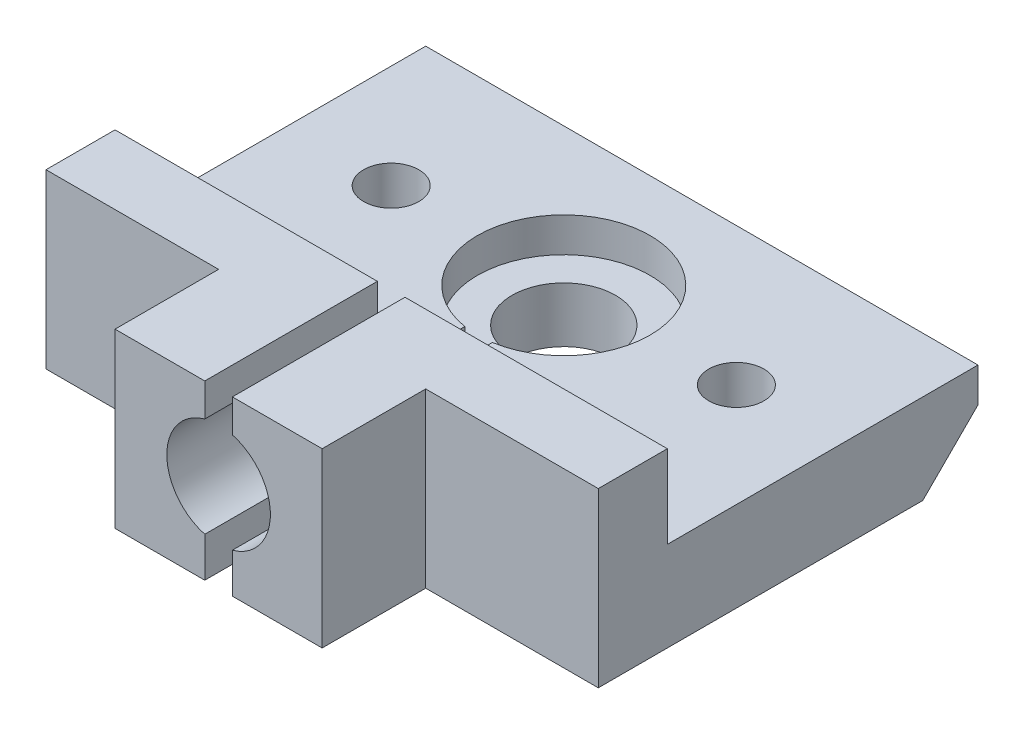
SolidWorks part; units mm, degrees
material "1060 Alloy"
ref_plane "Front Plane" through (0, 0, 0) normal (0, 0, 1) x (1, 0, 0)
ref_plane "Top Plane" through (0, 0, 0) normal (0, 1, 0) x (1, 0, 0)
ref_plane "Right Plane" through (0, 0, 0) normal (1, 0, 0) x (0, 0, -1)
sketch "Sketch1" plane through (0, 0, 0) normal (0, 1, 0) x (1, 0, 0)
  line L0 (0, 0) -> (85.3601, 0) construction
  line L1 (25, 0) -> (55, 0)
  line L2 (0, 15) -> (0, 70)
  line L3 (0, 70) -> (80, 70)
  line L4 (80, 15) -> (80, 70)
  line L7 (0, 15) -> (25, 15)
  line L8 (25, 0) -> (25, 15)
  line L10 (55, 0) -> (55, 15)
  line L11 (55, 15) -> (80, 15)
  line L13 (0, 0) -> (0, 88.5762) construction
  dimension "D1" = 80
  dimension "D2" = 70
  dimension "D3" = 25
  dimension "D4" = 25
  dimension "D5" = 15
  dimension "D6" = 15
extrude "Boss-Extrude1" add sketch "Sketch1" along normal blind 25 contours L4 L3 L2 L7 L8 L1 L10 L11
sketch "Sketch2" plane through (0, 0, 0) normal (1, 0, 0) x (0, 0, -1)
  line L1 (70, 25) -> (25, 25)
  line L2 (70, 25) -> (70, 13)
  line L3 (70, 13) -> (25, 13)
  line L4 (25, 25) -> (25, 13)
  dimension "D1" = 45
  dimension "D2" = 12
extrude "Cut-Extrude2" cut sketch "Sketch2" against normal through all and the other way through all contours L3 L4 L1 L2
chamfer "Chamfer1" distance 8 angle 45 1 edges at (40, 0, -70)
sketch "Sketch3" plane through (0, 13, 0) normal (0, 1, 0) x (1, 0, 0)
  line L0 (40, 0) -> (40, 55.2603) construction
  line L1 (25, 0) -> (55, 0) construction
  line L2 (0, 25) -> (80, 25) construction
  circle A0 centre (40, 50) radius 7.5
  circle A1 centre (65, 50) radius 4
  circle A2 centre (15, 50) radius 4
  point P10 (0, 0)
  dimension "D3" = 8
  dimension "D4" = 8
  dimension "D5" = 15
  dimension "D1" = 25
  dimension "D2" = 25
  dimension "D6" = 25
extrude "Cut-Extrude3" cut sketch "Sketch3" against normal blind 25
sketch "Sketch4" plane through (0, 13, 0) normal (0, 1, 0) x (1, 0, 0)
  circle A0 centre (40, 50) radius 12.5
  dimension "D1" = 25
extrude "Cut-Extrude4" cut sketch "Sketch4" against normal blind 5 contours A0
sketch "Sketch5" plane through (0, 25, 0) normal (0, 1, 0) x (1, 0, 0)
  line L0 (40, 0) -> (40, 46.2452) construction
  line L1 (25, 0) -> (55, 0) construction
  line L3 (38, -1.2028) -> (42, -1.2028)
  line L4 (38, -1.2028) -> (38, 51.5593)
  line L5 (38, 51.5593) -> (42, 51.5593)
  line L6 (42, -1.2028) -> (42, 51.5593)
  line L7 (38, -1.2028) -> (42, 51.5593) construction
  line L8 (38, 51.5593) -> (42, -1.2028) construction
  point P4 (40, 25.1783)
  dimension "D1" = 4
extrude "Cut-Extrude5" cut sketch "Sketch5" against normal through all contours L6 L5 L4 L3
sketch "Sketch6" plane through (0, 0, 0) normal (0, 0, 1) x (1, 0, 0)
  line L0 (52.5, 13) -> (27.5, 13) construction
  line L1 (42, 0) -> (55, 0) construction
  line L2 (55, 25) -> (80, 25) construction
  circle A0 centre (40, 13) radius 7.5
  dimension "D1" = 15
  dimension "D2" = 13
  dimension "D3" = 12
extrude "Cut-Extrude6" cut sketch "Sketch6" against normal blind 15
